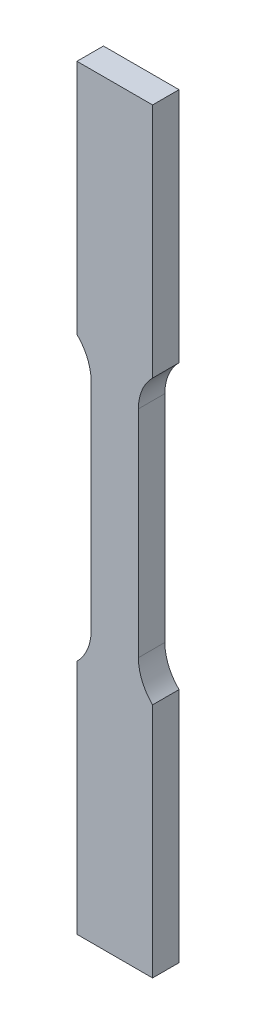
SolidWorks part; units mm, degrees
ref_plane "Front Plane" through (0, 0, 0) normal (0, 0, 1) x (1, 0, 0)
ref_plane "Top Plane" through (0, 0, 0) normal (0, 1, 0) x (1, 0, 0)
ref_plane "Right Plane" through (0, 0, 0) normal (1, 0, 0) x (0, 0, -1)
sketch "Sketch1" plane through (0, 0, 0) normal (0, 0, 1) x (1, 0, 0)
  line L1 (-10, -100) -> (10, -100)
  line L2 (-10, -100) -> (-10, 100)
  line L3 (-10, 100) -> (10, 100)
  line L4 (10, -100) -> (10, 100)
  line L5 (-10, -100) -> (10, 100) construction
  line L6 (-10, 100) -> (10, -100) construction
  point P0 (0, 0)
  dimension "D1" = 200
  dimension "D2" = 20
extrude "Boss-Extrude1" add sketch "Sketch1" along normal mid plane 7
sketch "Sketch2" plane through (0, 0, 3.5) normal (0, 0, 1) x (1, 0, 0)
  line L0 (0, -100) -> (0, 100) construction
  line L1 (10, 100) -> (-10, 100) construction
  line L2 (6.25, -28.5) -> (6.25, 28.5)
  line L3 (-6.25, -28.5) -> (-6.25, 28.5)
  line L5 (-10, 0) -> (10, 0) construction
  line L6 (10, -100) -> (10, 100) construction
  line L7 (-10, 19.5732) -> (-10, -19.5732)
  line L8 (-10, 100) -> (-10, -100) construction
  line L9 (10, -19.5732) -> (10, 19.5732)
  circle A0 centre (18.75, 28.5) radius 12.5
  circle A1 centre (18.75, -28.5) radius 12.5
  circle A2 centre (-18.75, -28.5) radius 12.5
  circle A3 centre (-18.75, 28.5) radius 12.5
  point P6 (0, 0)
  point P9 (6.25, 0)
  point P21 (0, 0)
  line M3 (10, -100) -> (10, 100)
  line M5 (-10, 100) -> (-10, -100)
  dimension "D3" = 12.5
  dimension "D1" = 6.25
  dimension "D2" = 57
extrude "Cut-Extrude1" cut sketch "Sketch2" against normal blind 7.112 contours A3 M5 | A0 M3 | L2 A1 A0 M3 | L3 A3 A2 M5 | A2 M5 | A1 M3
sketch "Sketch3" plane through (0, 0, -3.5) normal (0, 0, -1) x (-1, 0, 0)
  line L0 (-10, 0) -> (10, 0) construction
  line L1 (10, 100) -> (10, 37.4268) construction
  line L2 (0, 100) -> (0, -100) construction
  line L3 (10, -100) -> (-10, -100) construction
  line L4 (6.25, 28.5) -> (6.25, -28.5)
  line L5 (-10, 100) -> (10, 100) construction
  line L6 (10, 50) -> (10, -50)
  line L7 (-10, 50) -> (-10, -50)
  line L8 (-6.25, 28.5) -> (-6.25, -28.5)
  arc A0 (6.25, 28.5) -> (10, 50) centre (14.1312, 38.2024) cw
  arc A1 (6.25, -28.5) -> (10, -50) centre (14.1312, -38.2024) ccw
  arc A2 (-6.25, 28.5) -> (-10, 50) centre (-14.1312, 38.2024) ccw
  arc A3 (-6.25, -28.5) -> (-10, -50) centre (-14.1312, -38.2024) cw
  point P6 (0, 0)
  point P11 (0, 0)
  point P13 (6.25, 0)
  dimension "D3" = 12.5
  dimension "D1" = 6.25
  dimension "D2" = 57
  dimension "D4" = 50
extrude "Cut-Extrude2" [suppressed] cut sketch "Sketch3" against normal through all both and the other way through all
equation "\"G\"= 50mm'Gage Length"
equation "\"W\"= 12.5mm'Width of Reduced Section"
equation "\"T\"= 7mm'Thickness of Material"
equation "\"R\"= 12.5mm'Radius of Fillet"
equation "\"L\"= 200mm'Overall Length"
equation "\"A\"= 57mm'Length of Reduced Section"
equation "\"B\"= 50mm'Length of Grip Section"
equation "\"C\"= 20mm'Width of Grip Section"
equation "\"D1@Sketch1\"=\"L\""
equation "\"D2@Sketch1\"=\"C\""
equation "\"D1@Boss-Extrude1\"=\"T\""
equation "\"D1@Sketch2\"=\"W\"/2"
equation "\"D2@Sketch2\"=\"A\""
equation "\"D3@Sketch2\"=\"R\""
equation "\"D1@Sketch3\"=\"W\"/2"
equation "\"D2@Sketch3\"=\"A\""
equation "\"D3@Sketch3\"=\"R\""
equation "\"D4@Sketch3\"=\"B\""
